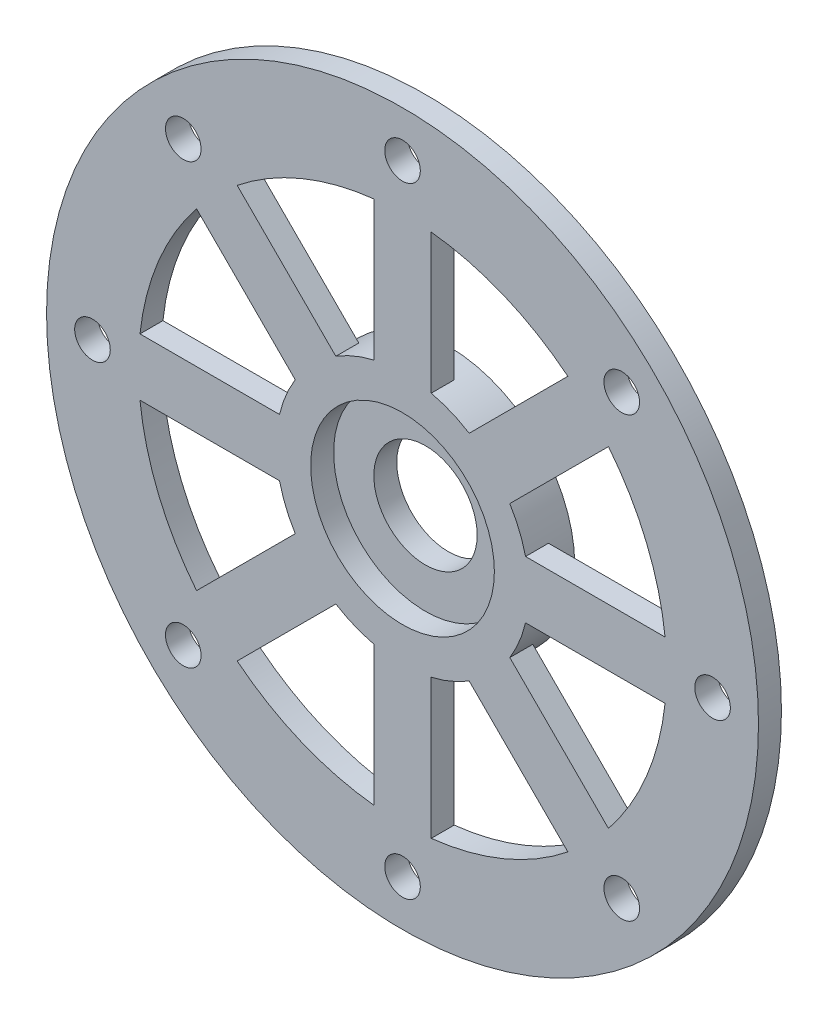
SolidWorks part; units mm, degrees
ref_plane "Front Plane" through (0, 0, 0) normal (0, 0, 1) x (1, 0, 0)
ref_plane "Top Plane" through (0, 0, 0) normal (0, 1, 0) x (1, 0, 0)
ref_plane "Right Plane" through (0, 0, 0) normal (1, 0, 0) x (0, 0, -1)
sketch "Sketch1" plane through (0, 0, 0) normal (0, 0, 1) x (1, 0, 0)
  line L0 (0, 0) -> (-27, 0) construction
  line L1 (-11, -2.5) -> (-11, 2.5) construction
  line L2 (-10.7121, 2.5) -> (-22.8637, 2.5)
  line L3 (-10.7121, -2.5) -> (-22.8637, -2.5)
  line L4 (-5.8069, 9.3424) -> (-14.3993, 17.9349)
  line L5 (-9.3424, 5.8069) -> (-17.9349, 14.3993)
  line L6 (2.5, 10.7121) -> (2.5, 22.8637)
  line L7 (-2.5, 10.7121) -> (-2.5, 22.8637)
  line L8 (9.3424, 5.8069) -> (17.9349, 14.3993)
  line L9 (5.8069, 9.3424) -> (14.3993, 17.9349)
  line L10 (10.7121, -2.5) -> (22.8637, -2.5)
  line L11 (10.7121, 2.5) -> (22.8637, 2.5)
  line L12 (5.8069, -9.3424) -> (14.3993, -17.9349)
  line L13 (9.3424, -5.8069) -> (17.9349, -14.3993)
  line L14 (-2.5, -10.7121) -> (-2.5, -22.8637)
  line L15 (2.5, -10.7121) -> (2.5, -22.8637)
  line L16 (-9.3424, -5.8069) -> (-17.9349, -14.3993)
  line L17 (-5.8069, -9.3424) -> (-14.3993, -17.9349)
  circle A0 centre (0, 0) radius 31
  circle A1 centre (-27, 0) radius 1.55
  circle A2 centre (-19.0919, 19.0919) radius 1.55
  circle A3 centre (0, 27) radius 1.55
  circle A4 centre (19.0919, 19.0919) radius 1.55
  circle A5 centre (27, 0) radius 1.55
  circle A6 centre (19.0919, -19.0919) radius 1.55
  circle A7 centre (0, -27) radius 1.55
  circle A8 centre (-19.0919, -19.0919) radius 1.55
  arc A9 (-22.8637, -2.5) -> (-17.9349, -14.3993) centre (0, 0) ccw
  arc A10 (-10.7121, -2.5) -> (-9.3424, -5.8069) centre (0, 0) ccw
  arc A11 (-17.9349, 14.3993) -> (-22.8637, 2.5) centre (0, 0) ccw
  arc A12 (-9.3424, 5.8069) -> (-10.7121, 2.5) centre (0, 0) ccw
  arc A13 (-2.5, 10.7121) -> (-5.8069, 9.3424) centre (0, 0) ccw
  arc A14 (-2.5, 22.8637) -> (-14.3993, 17.9349) centre (0, 0) ccw
  arc A15 (14.3993, 17.9349) -> (2.5, 22.8637) centre (0, 0) ccw
  arc A16 (5.8069, 9.3424) -> (2.5, 10.7121) centre (0, 0) ccw
  arc A17 (10.7121, 2.5) -> (9.3424, 5.8069) centre (0, 0) ccw
  arc A18 (9.3424, -5.8069) -> (10.7121, -2.5) centre (0, 0) ccw
  arc A19 (2.5, -10.7121) -> (5.8069, -9.3424) centre (0, 0) ccw
  arc A20 (-5.8069, -9.3424) -> (-2.5, -10.7121) centre (0, 0) ccw
  arc A21 (22.8637, 2.5) -> (17.9349, 14.3993) centre (0, 0) ccw
  arc A22 (17.9349, -14.3993) -> (22.8637, -2.5) centre (0, 0) ccw
  arc A23 (2.5, -22.8637) -> (14.3993, -17.9349) centre (0, 0) ccw
  arc A24 (-14.3993, -17.9349) -> (-2.5, -22.8637) centre (0, 0) ccw
  point P5 (0, 0)
  point P21 (0, 0)
  point P25 (-11, 0)
  point P57 (0, 0)
  dimension "D1" = 8
  dimension "D2" = 8
extrude "Boss-Extrude1" add sketch "Sketch1" along normal blind 2
sketch "Sketch3" plane through (0, 0, 0) normal (0, 0, -1) x (-1, 0, 0)
  circle A0 centre (0, 0) radius 11
extrude "Boss-Extrude2" add sketch "Sketch3" along normal blind 2
sketch "Sketch4" plane through (0, 0, 2) normal (0, 0, 1) x (1, 0, 0)
  circle A0 centre (0, 0) radius 4.5
extrude "Cut-Extrude2" cut sketch "Sketch4" against normal up to surface (4 mm away) up to face at (-11, 0, -2)
sketch "Sketch2" plane through (0, 0, 2) normal (0, 0, 1) x (1, 0, 0)
  circle A0 centre (0, 0) radius 8
extrude "Cut-Extrude1" cut sketch "Sketch2" against normal blind 2
